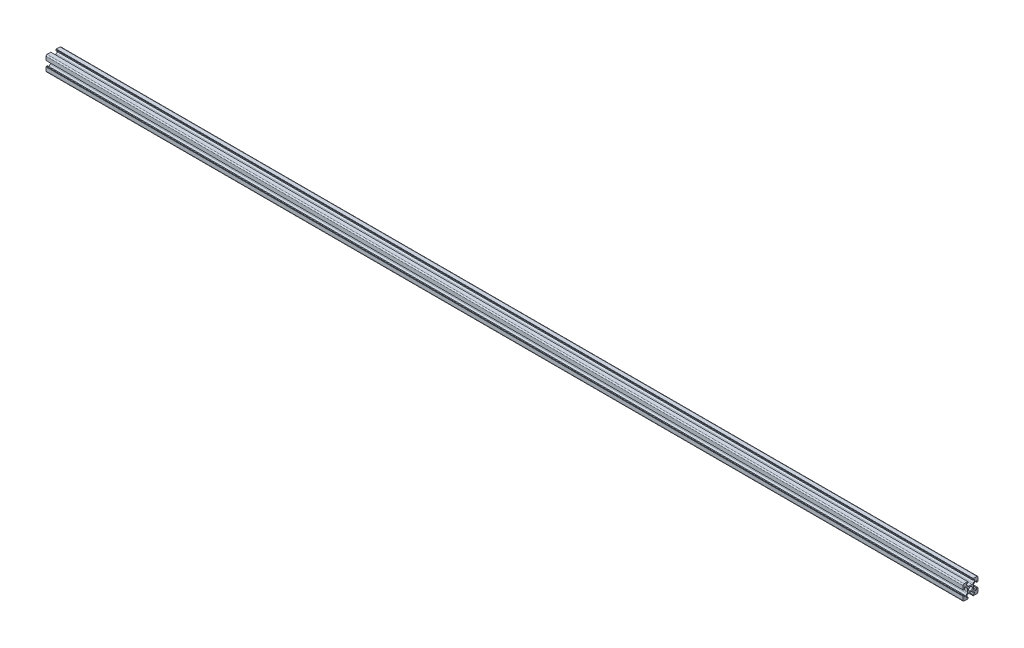
SolidWorks part; units mm, degrees
ref_plane "Front Plane" through (0, 0, 0) normal (1, 0, 0) x (0, 1, 0)
ref_plane "Top Plane" through (0, 0, 0) normal (0, 0, 1) x (0, 1, 0)
ref_plane "Right Plane" through (0, 0, 0) normal (0, 1, 0) x (-1, 0, 0)
sketch "Sketch2" plane through (0, 0, 0) normal (1, 0, 0) x (0, 1, 0)
  line L0 (-10, 3.6) -> (-9.5, 3.6)
  line L1 (-2.0109, -3.9) -> (2.0109, -3.9)
  line L2 (-3.9, -2.0109) -> (-3.9, 2.0109)
  line L3 (-2.0109, 3.9) -> (2.0109, 3.9)
  line L4 (3.9, -2.0109) -> (3.9, 2.0109)
  line L5 (-3.9, -3.9) -> (3.9, 3.9) construction
  line L6 (-3.9, 3.9) -> (3.9, -3.9) construction
  line L7 (-8.5, -10) -> (-3.6, -10)
  line L8 (-10, -8.5) -> (-10, -3.6)
  line L9 (-8.5, 10) -> (-3.6, 10)
  line L10 (10, -8.5) -> (10, -3.6)
  line L11 (-10, -10) -> (10, 10) construction
  line L12 (-10, 10) -> (10, -10) construction
  line L13 (-9.5, 3.6) -> (-9.5, 3.1)
  line L14 (-9.5, 3.1) -> (-8.2, 3.1)
  line L15 (-8.2, 3.1) -> (-8.2, 5.5)
  line L16 (-8.2, 5.5) -> (-6.5607, 5.5)
  line L17 (-6.5607, 5.5) -> (-4.4858, 3.4251)
  line L18 (3.6, 10) -> (3.6, 9.5)
  line L19 (-3.1, 9.5) -> (-3.1, 8.2)
  line L20 (-3.6, 9.5) -> (-3.1, 9.5)
  line L21 (-3.6, 10) -> (-3.6, 9.5)
  line L22 (-3.1, 8.2) -> (-5.5, 8.2)
  line L23 (-5.5, 8.2) -> (-5.5, 6.5607)
  line L24 (-5.5, 6.5607) -> (-3.4251, 4.4858)
  line L25 (3.6, 9.5) -> (3.1, 9.5)
  line L26 (3.1, 9.5) -> (3.1, 8.2)
  line L27 (3.1, 8.2) -> (5.5, 8.2)
  line L28 (5.5, 8.2) -> (5.5, 6.5607)
  line L29 (5.5, 6.5607) -> (3.4251, 4.4858)
  line L30 (6.5607, 5.5) -> (4.4858, 3.4251)
  line L31 (8.2, 5.5) -> (6.5607, 5.5)
  line L32 (8.2, 3.1) -> (8.2, 5.5)
  line L33 (9.5, 3.1) -> (8.2, 3.1)
  line L34 (9.5, 3.6) -> (9.5, 3.1)
  line L35 (10, 3.6) -> (9.5, 3.6)
  line L36 (10, -3.6) -> (9.5, -3.6)
  line L37 (9.5, -3.6) -> (9.5, -3.1)
  line L38 (9.5, -3.1) -> (8.2, -3.1)
  line L39 (8.2, -3.1) -> (8.2, -5.5)
  line L40 (8.2, -5.5) -> (6.5607, -5.5)
  line L41 (6.5607, -5.5) -> (4.4858, -3.4251)
  line L42 (5.5, -6.5607) -> (3.4251, -4.4858)
  line L43 (5.5, -8.2) -> (5.5, -6.5607)
  line L44 (3.1, -8.2) -> (5.5, -8.2)
  line L45 (3.1, -9.5) -> (3.1, -8.2)
  line L46 (3.6, -9.5) -> (3.1, -9.5)
  line L47 (3.6, -10) -> (3.6, -9.5)
  line L48 (-3.6, -10) -> (-3.6, -9.5)
  line L49 (-3.6, -9.5) -> (-3.1, -9.5)
  line L50 (-3.1, -9.5) -> (-3.1, -8.2)
  line L51 (-3.1, -8.2) -> (-5.5, -8.2)
  line L52 (-5.5, -8.2) -> (-5.5, -6.5607)
  line L53 (-5.5, -6.5607) -> (-3.4251, -4.4858)
  line L54 (-6.5607, -5.5) -> (-4.4858, -3.4251)
  line L55 (-8.2, -5.5) -> (-6.5607, -5.5)
  line L56 (-8.2, -3.1) -> (-8.2, -5.5)
  line L57 (-9.5, -3.1) -> (-8.2, -3.1)
  line L58 (-9.5, -3.6) -> (-9.5, -3.1)
  line L59 (-10, -3.6) -> (-9.5, -3.6)
  line L60 (-10, 3.6) -> (-10, 8.5)
  line L61 (3.6, 10) -> (8.5, 10)
  line L62 (10, 3.6) -> (10, 8.5)
  line L63 (3.6, -10) -> (8.5, -10)
  circle A0 centre (0, 0) radius 2.5
  arc A1 (-8.5, -10) -> (-10, -8.5) centre (-8.5, -8.5) cw
  arc A2 (8.5, 10) -> (10, 8.5) centre (8.5, 8.5) cw
  arc A3 (8.5, -10) -> (10, -8.5) centre (8.5, -8.5) ccw
  arc A4 (-10, 8.5) -> (-8.5, 10) centre (-8.5, 8.5) cw
  arc A5 (-4.4858, 3.4251) -> (-3.9, 2.0109) centre (-5.9, 2.0109) cw
  arc A6 (-4.4858, -3.4251) -> (-3.9, -2.0109) centre (-5.9, -2.0109) ccw
  arc A7 (-3.4251, -4.4858) -> (-2.0109, -3.9) centre (-2.0109, -5.9) cw
  arc A8 (3.4251, -4.4858) -> (2.0109, -3.9) centre (2.0109, -5.9) ccw
  arc A9 (4.4858, -3.4251) -> (3.9, -2.0109) centre (5.9, -2.0109) cw
  arc A10 (4.4858, 3.4251) -> (3.9, 2.0109) centre (5.9, 2.0109) ccw
  arc A11 (3.4251, 4.4858) -> (2.0109, 3.9) centre (2.0109, 5.9) cw
  arc A12 (-3.4251, 4.4858) -> (-2.0109, 3.9) centre (-2.0109, 5.9) ccw
  point P82 (0, 0)
  point P88 (-3.9, 2.8393)
  point P103 (-2.8393, 3.9)
  dimension "D1" = 5
  dimension "D6" = 1.5
  dimension "D14" = 2
  dimension "D15" = 2
  dimension "D2" = 7.8
  dimension "D3" = 7.8
  dimension "D4" = 20
  dimension "D5" = 20
  dimension "D8" = 1.5
  dimension "D9" = 11
  dimension "D10" = 7.2
  dimension "D11" = 6.2
  dimension "D12" = 0.5
  dimension "D13" = 1.8
  dimension "D16" = 3.9
  dimension "D17" = 3.9
  dimension "D7" = 4
extrude "Boss-Extrude1" add sketch "Sketch2" along normal mid plane 1219.2
